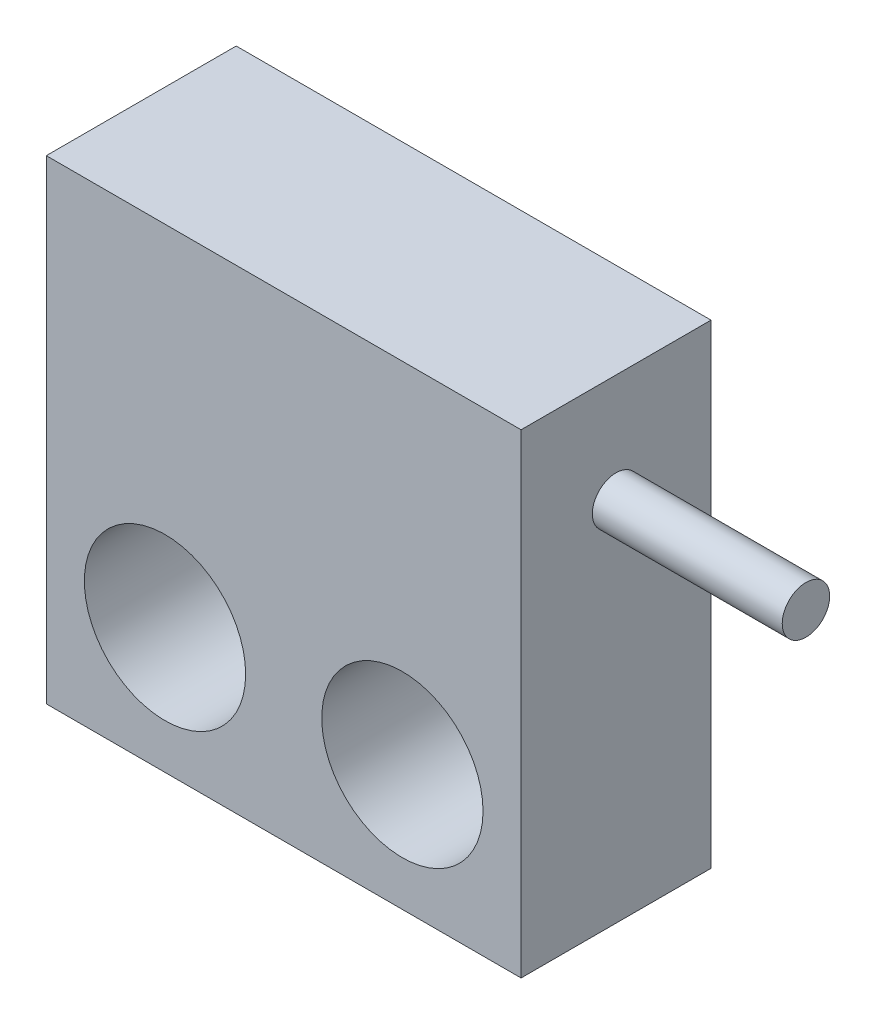
SolidWorks part; units mm, degrees
ref_plane "Front Plane" through (0, 0, 0) normal (0, 0, 1) x (1, 0, 0)
ref_plane "Top Plane" through (0, 0, 0) normal (0, 1, 0) x (1, 0, 0)
ref_plane "Right Plane" through (0, 0, 0) normal (1, 0, 0) x (0, 0, -1)
sketch "Sketch7" plane through (0, 0, 0) normal (0, 0, 1) x (1, 0, 0)
  line L1 (0, 0) -> (50, 0)
  line L2 (0, 0) -> (0, 50)
  line L3 (0, 50) -> (50, 50)
  line L4 (50, 0) -> (50, 50)
  circle A0 centre (12.5, 13.2102) radius 8.4932
  circle A1 centre (37.5, 13.2102) radius 8.4932
  dimension "D3" = 12.5
  dimension "D4" = 12.5
  dimension "D1" = 50
  dimension "D2" = 50
extrude "Boss-Extrude4" add sketch "Sketch7" along normal blind 20
sketch "Sketch8" plane through (50, 0, 0) normal (1, 0, 0) x (0, 0, -1)
  line L0 (-10, 0) -> (-10, 50) construction
  line L1 (-20, 0) -> (0, 0) construction
  line L2 (-20, 50) -> (0, 50) construction
  circle A0 centre (-10, 38.578) radius 2.5
  dimension "D1" = 5
extrude "Boss-Extrude5" add sketch "Sketch8" along normal blind 20
